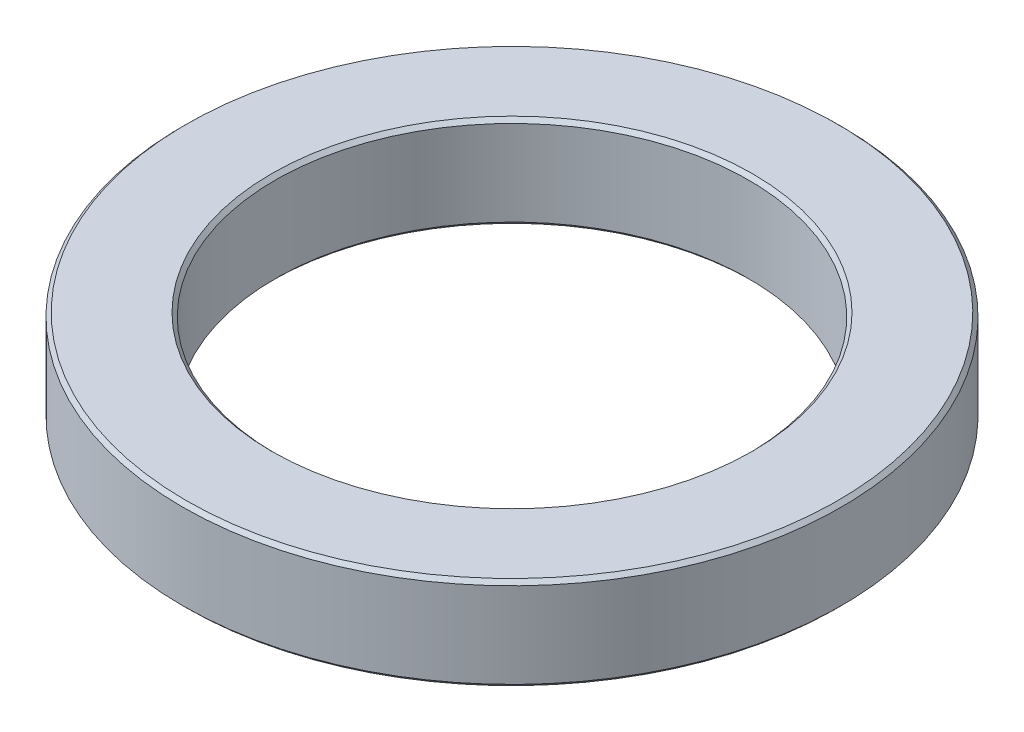
SolidWorks part; units mm, degrees
material "AISI 304"
ref_plane "Front" through (0, 0, 0) normal (0, 0, 1) x (1, 0, 0)
ref_plane "Top" through (0, 0, 0) normal (0, 1, 0) x (1, 0, 0)
ref_plane "Right" through (0, 0, 0) normal (1, 0, 0) x (0, 0, -1)
sketch "Sketch1" plane through (0, 0, 0) normal (0, 1, 0) x (1, 0, 0)
  circle A0 centre (0, 0) radius 17.75
  circle A1 centre (0, 0) radius 12.75
  dimension "D1" = 35.5
  dimension "D2" = 25.5
  dimension "D3" = 5
extrude "Boss-Extrude1" add sketch "Sketch1" along normal blind 5
chamfer "Chamfer1" distance 0.2 angle 45 4 edges at (0, 0, 12.75) (0, 0, 17.75) (0, 5, 12.75) (0, 5, 17.75)
